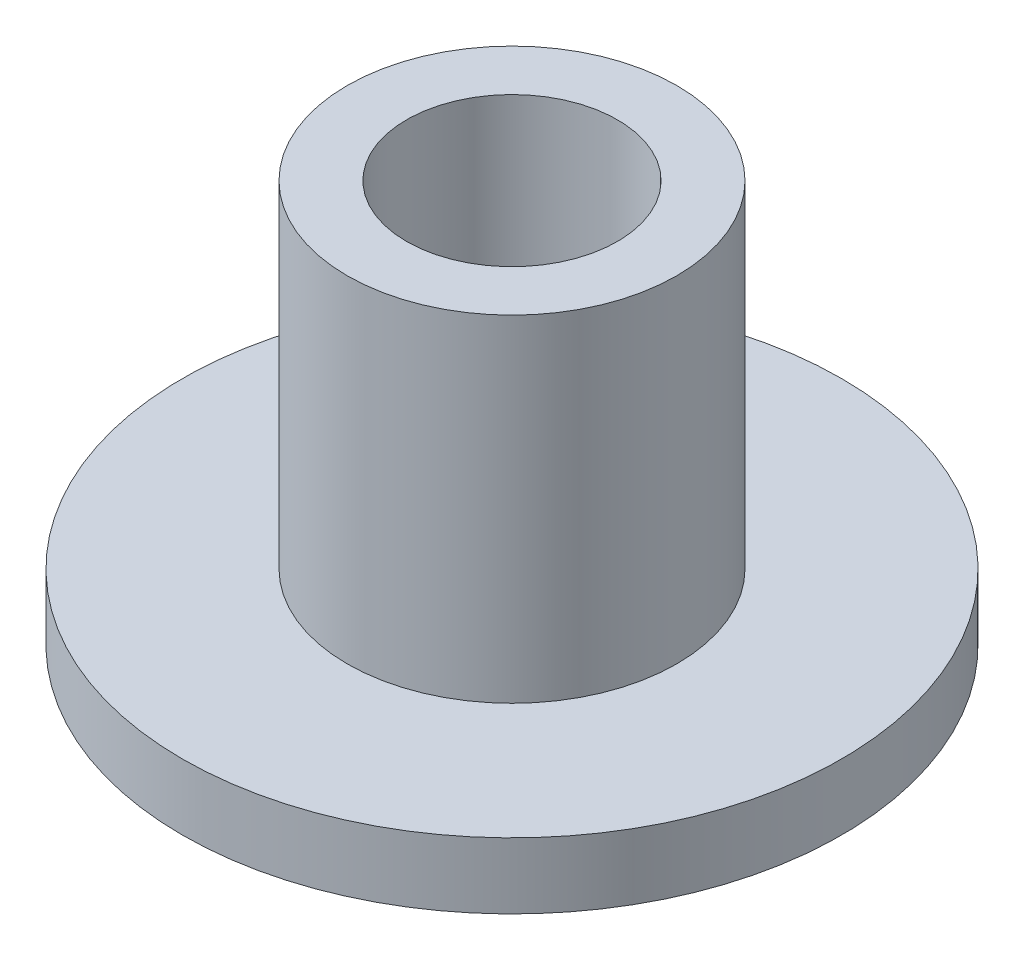
SolidWorks part; units mm, degrees
ref_plane "Front Plane" through (0, 0, 0) normal (0, 0, 1) x (1, 0, 0)
ref_plane "Top Plane" through (0, 0, 0) normal (0, 1, 0) x (1, 0, 0)
ref_plane "Right Plane" through (0, 0, 0) normal (1, 0, 0) x (0, 0, -1)
sketch "Sketch1" plane through (0, 0, 0) normal (0, 1, 0) x (1, 0, 0)
  circle A0 centre (0, 0) radius 5
  dimension "D1" = 10
extrude "Boss-Extrude1" add sketch "Sketch1" along normal blind 6.1
hole_wizard "M3 Clearance Hole1" positions "Sketch3" profile "Sketch2" hole size "M3" standard "ISO" end condition through all
sketch "Sketch3" plane through (0, 6.1, 0) normal (0, 1, 0) x (-1, 0, 0)
  point P0 (0, 0)
sketch "Sketch2" plane through (0, 6.1, 0) normal (1, 0, 0) x (0, 0, 1)
  line L0 (0, 0) -> (0, 6.1)
  line L1 (0, 6.1) -> (1.6, 6.1)
  line L2 (1.6, 6.1) -> (1.6, 0)
  line L5 (1.6, 0) -> (0, 0)
  line L11 (0, -6.35) -> (0, 107.95) construction
  dimension "Thru Hole Dia." = 3.2
  dimension "Thru Hole Depth" = 6.1
sketch "Sketch4" plane through (0, 6.1, 0) normal (0, 1, 0) x (1, 0, 0)
  circle A0 centre (0, 0) radius 2.5
  circle A1 centre (0, 0) radius 5.8081
  dimension "D1" = 5
extrude "Cut-Extrude1" cut sketch "Sketch4" against normal blind 5.1
